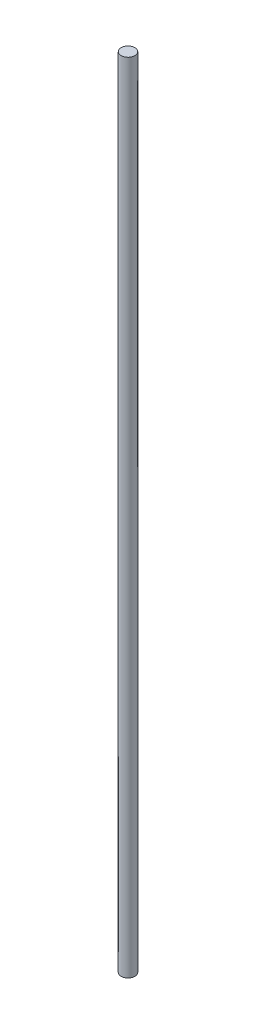
SolidWorks part; units mm, degrees
ref_plane "Płaszczyzna przednia" through (0, 0, 0) normal (0, 0, 1) x (1, 0, 0)
ref_plane "Płaszczyzna górna" through (0, 0, 0) normal (0, 1, 0) x (1, 0, 0)
ref_plane "Płaszczyzna prawa" through (0, 0, 0) normal (1, 0, 0) x (0, 0, -1)
sketch "Szkic1" plane through (0, 0, 0) normal (0, 1, 0) x (1, 0, 0)
  circle A0 centre (0, 0) radius 1.125
  dimension "D1" = 2.25
extrude "Dodanie-wyciągnięcie1" add sketch "Szkic1" along normal blind 130
